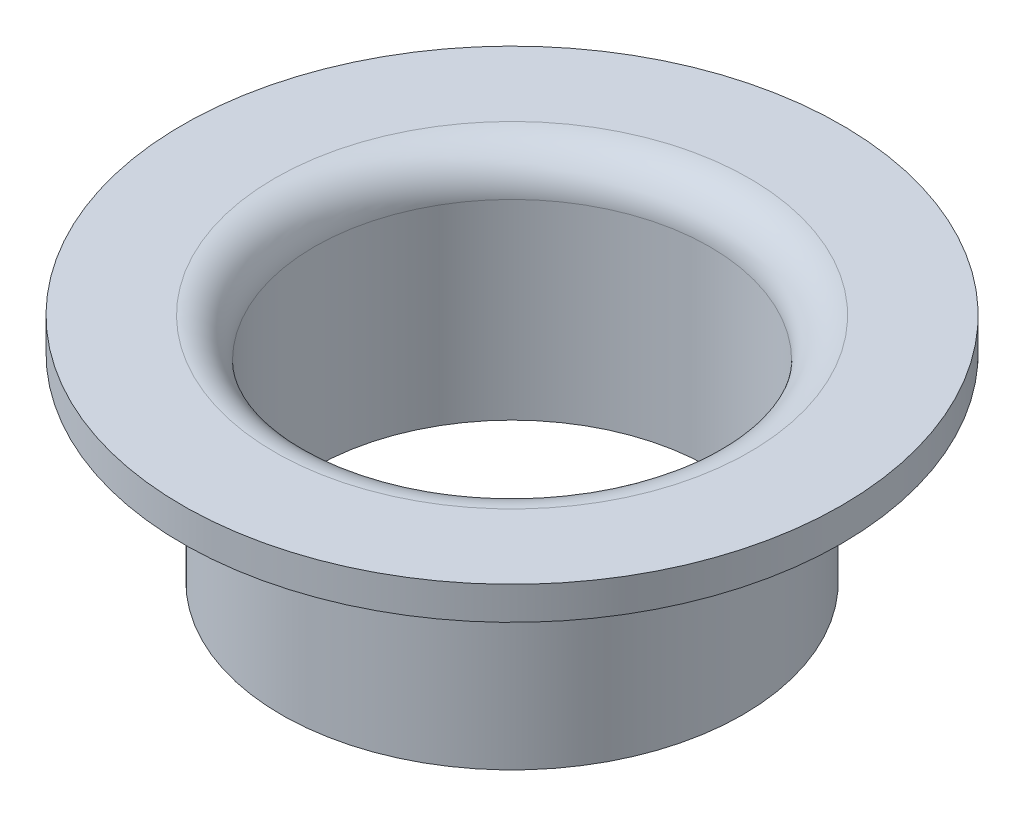
SolidWorks part; units mm, degrees
ref_plane "Plan1" through (0, 0, 0) normal (0, 0, 1) x (1, 0, 0)
ref_plane "Plan2" through (0, 0, 0) normal (0, 1, 0) x (1, 0, 0)
ref_plane "Plan3" through (0, 0, 0) normal (1, 0, 0) x (0, 0, -1)
ref_plane "Plan4" through (0, -0.0005, 1021.1011) normal (0, 0, 1) x (1, 0, 0)
sketch "Esquisse1" plane through (0, -0.0005, 1021.1011) normal (0, 0, 1) x (1, 0, 0)
  line L0 (1715.4014, 541.9989) -> (1711.4014, 541.9992)
  line L1 (1711.4014, 541.9992) -> (1711.4009, 534.9992)
  line L2 (1711.4009, 534.9992) -> (1712.4009, 534.9991)
  line L3 (1712.4009, 534.9991) -> (1712.4014, 540.9991)
  line L4 (1712.4014, 540.9991) -> (1715.4014, 540.9989)
  line L5 (1715.4014, 540.9989) -> (1715.4014, 541.9989)
  line L6 (1705.4014, 542.0004) -> (1705.4009, 534.9995) construction
  dimension "D1" = 12
  dimension "D2" = 14
  dimension "D3" = 20
  dimension "D4" = 1
  dimension "D5" = 6
revolve "Base-Révolution" add sketch "Esquisse1" angle 360 about L6
fillet "Congé0.2" radius 0.2
fillet "Congé1.2" radius 1.2
